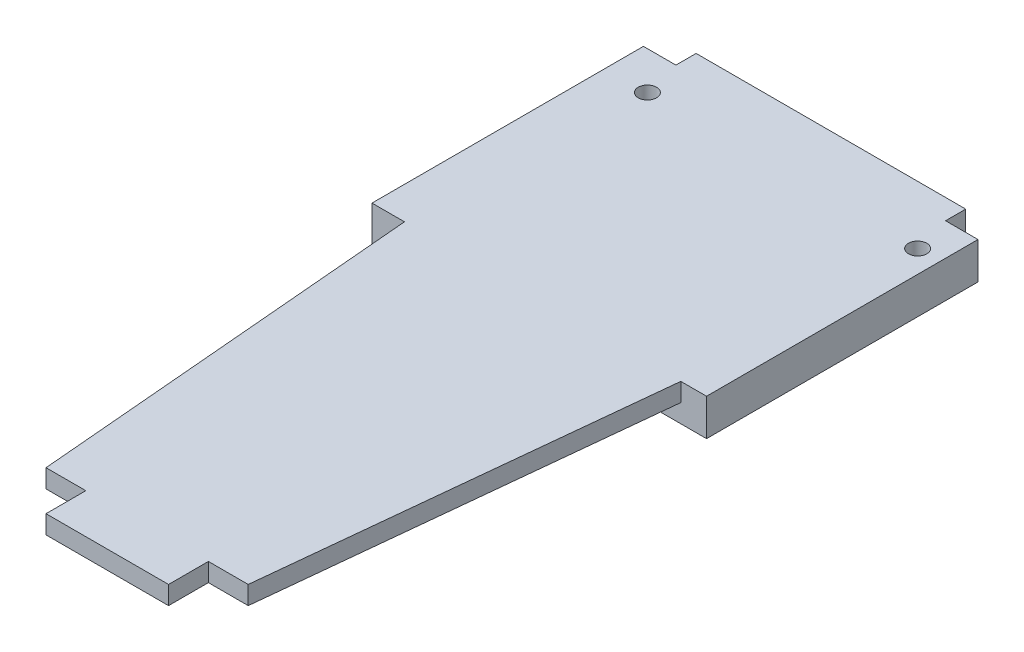
SolidWorks part; units mm, degrees
ref_plane "Front Plane" through (0, 0, 0) normal (0, 0, 1) x (1, 0, 0)
ref_plane "Top Plane" through (0, 0, 0) normal (0, 1, 0) x (1, 0, 0)
ref_plane "Right Plane" through (0, 0, 0) normal (1, 0, 0) x (0, 0, -1)
sketch "Sketch1" plane through (0, 0, 0) normal (0, 1, 0) x (1, 0, 0)
  line L0 (-16.5, 0) -> (-10, 0)
  line L1 (0, 0) -> (0, 64) construction
  line L3 (0, 64) -> (0, 86.8) construction
  line L4 (-27.3, 86.8) -> (27.3, 86.8)
  line L5 (16.5, 0) -> (23.1, 64)
  line L6 (-16.5, 0) -> (-22, 64)
  line L7 (-27.3, 64) -> (27.3, 64)
  line L8 (-27.3, 64) -> (-27.3, 86.8)
  line L9 (27.3, 64) -> (27.3, 86.8)
  line L10 (0, 89.8) -> (0, 108.3)
  line L17 (-27.3, 86.8) -> (-27.3, 108.3)
  line L18 (-10, 0) -> (-10, -6.5)
  line L19 (-10, -6.5) -> (10, -6.5)
  line L20 (-27.3, 108.3) -> (27.3, 108.3)
  line L21 (27.3, 86.8) -> (27.3, 108.3)
  line L24 (0, 108.3) -> (0, 111.6)
  line L25 (-22, 111.6) -> (22, 111.6)
  line L26 (-22, 111.6) -> (-22, 108.3)
  line L27 (22, 111.6) -> (22, 108.3)
  line L28 (10, -6.5) -> (10, 0)
  line L30 (10, 0) -> (16.5, 0)
  point P4 (0, 0)
  point P10 (0, 64)
  point P14 (0, 86.8)
  point P17 (0, 64)
  point P23 (0, 0)
  point P24 (0, 108.3)
  point P32 (0, 111.6)
  dimension "D12" = 64
  dimension "D17" = 6.5
  dimension "D7" = 21.5
  dimension "D1" = 33
  dimension "D2" = 45.1
  dimension "D3" = 54.6
  dimension "D4" = 64
  dimension "D5" = 44.3
  dimension "D6" = 54.6
  dimension "D8" = 18.5
  dimension "D9" = 3.3
  dimension "D10" = 20
  dimension "D11" = 10
  dimension "D13" = 5.3
  dimension "D14" = 0
  dimension "D15" = 44
  dimension "D16" = 23.1
extrude "Boss-Extrude1" add sketch "Sketch1" along normal blind 3
sketch "Sketch2" plane through (0, 0, 0) normal (0, -1, 0) x (1, 0, 0)
  line L0 (22.15, -100.6) -> (22.15, -120.6675) construction
  line L1 (31.9243, -100.6) -> (8.1509, -100.6) construction
  line L2 (-22, -111.6) -> (22, -111.6) construction
  line L3 (27.3, -64) -> (27.3, -108.3) construction
  line L4 (-21.95, -93.5652) -> (-21.95, -114.2218) construction
  line L5 (-30.5006, -100.6) -> (-7.7551, -100.6) construction
  line L6 (-27.3, -64) -> (-27.3, -108.3) construction
  circle A0 centre (23.65, -102.1) radius 1.5
  circle A1 centre (-20.45, -102.1) radius 1.5
  dimension "D3" = 3
  dimension "D6" = 3
  dimension "D1" = 11
  dimension "D2" = 5.15
  dimension "D4" = 5.35
  dimension "D5" = 11
extrude "Cut-Extrude1" cut sketch "Sketch2" against normal blind 3
sketch "Sketch3" plane through (0, 0, 0) normal (0, -1, 0) x (1, 0, 0)
  line L0 (-27.3, -108.3) -> (-22, -108.3) construction
  line L1 (-27.3, -64) -> (-27.3, -108.3) construction
  line L2 (-27.3, -64) -> (-22, -64) construction
  line L3 (23.1, -64) -> (27.3, -64) construction
  line L4 (27.3, -64) -> (27.3, -108.3) construction
  line L5 (22, -108.3) -> (27.3, -108.3) construction
  line L6 (22, -111.6) -> (22, -108.3) construction
  line L7 (-22, -111.6) -> (22, -111.6) construction
  line L8 (-27.3, -108.3) -> (-22, -108.3)
  line L9 (-27.3, -64) -> (-27.3, -108.3)
  line L10 (-27.3, -64) -> (-22, -64)
  line L11 (23.1, -64) -> (27.3, -64)
  line L12 (27.3, -64) -> (27.3, -108.3)
  line L13 (22, -108.3) -> (27.3, -108.3)
  line L14 (22, -111.6) -> (22, -108.3)
  line L15 (-22, -111.6) -> (22, -111.6)
  line L16 (-22, -64) -> (23.1, -64)
  circle A0 centre (23.65, -102.1) radius 1.5 construction
  circle A1 centre (-20.45, -102.1) radius 1.5 construction
  circle A2 centre (23.65, -102.1) radius 1.5
  circle A3 centre (-20.45, -102.1) radius 1.5
  circle M10 centre (23.65, -102.1) radius 1.5
  circle M11 centre (-20.45, -102.1) radius 1.5
  line M12 (22, -111.6) -> (22, -108.3)
  line M13 (22, -108.3) -> (27.3, -108.3)
  line M14 (27.3, -108.3) -> (27.3, -64)
  line M15 (27.3, -64) -> (23.1, -64)
  line M19 (-22, -64) -> (-27.3, -64)
  line M20 (-27.3, -64) -> (-27.3, -108.3)
  line M21 (-27.3, -108.3) -> (-22, -108.3)
  line M22 (-22, -108.3) -> (-22, -111.6)
  line M23 (-22, -111.6) -> (22, -111.6)
extrude "Boss-Extrude2" add sketch "Sketch3" along normal blind 3 contours L16 M19 M20 M21 M22 M23 M12 M13 M14 M15 M11 M10
